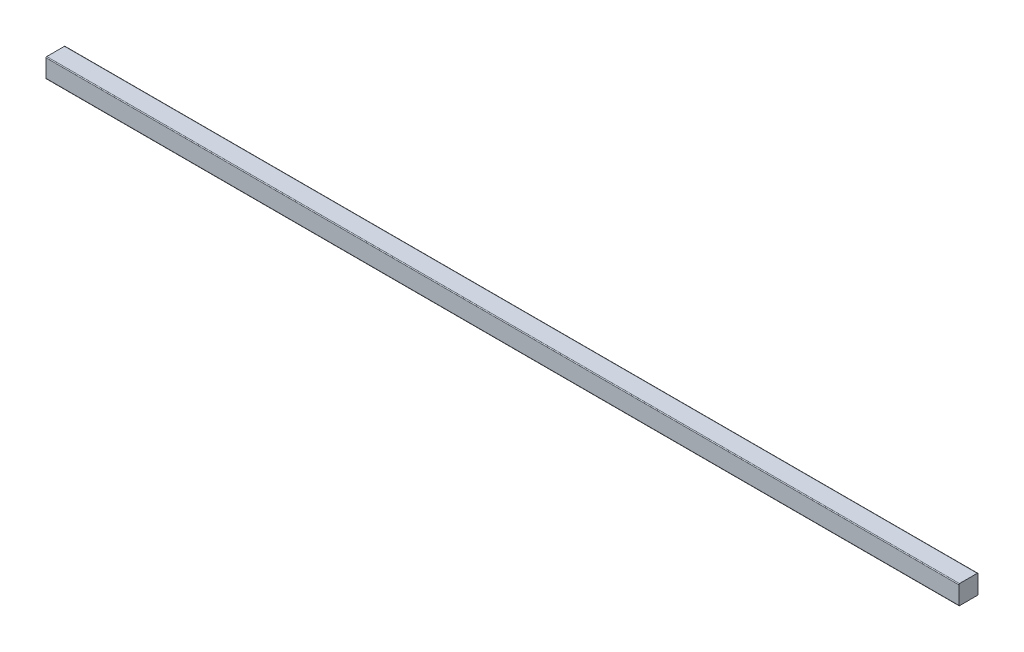
SolidWorks part; units mm, degrees
ref_plane "Front Plane" through (0, 0, 0) normal (0, 0, 1) x (1, 0, 0)
ref_plane "Top Plane" through (0, 0, 0) normal (0, 1, 0) x (1, 0, 0)
ref_plane "Right Plane" through (0, 0, 0) normal (1, 0, 0) x (0, 0, -1)
sketch "Sketch1" plane through (0, 0, 0) normal (1, 0, 0) x (0, 0, -1)
  line L1 (-3.175, -3.175) -> (3.175, -3.175)
  line L2 (-3.175, -3.175) -> (-3.175, 3.175)
  line L3 (-3.175, 3.175) -> (3.175, 3.175)
  line L4 (3.175, -3.175) -> (3.175, 3.175)
  line L5 (-3.175, -3.175) -> (3.175, 3.175) construction
  line L6 (-3.175, 3.175) -> (3.175, -3.175) construction
  point P0 (0, 0)
  dimension "D1" = 6.35
  dimension "D2" = 6.35
extrude "Boss-Extrude1" add sketch "Sketch1" along normal blind 301.625
fillet "Fillet1" radius 0.254 4 edges at (150.8125, -3.175, -3.175) (150.8125, -3.175, 3.175) (150.8125, 3.175, 3.175) (150.8125, 3.175, -3.175)
